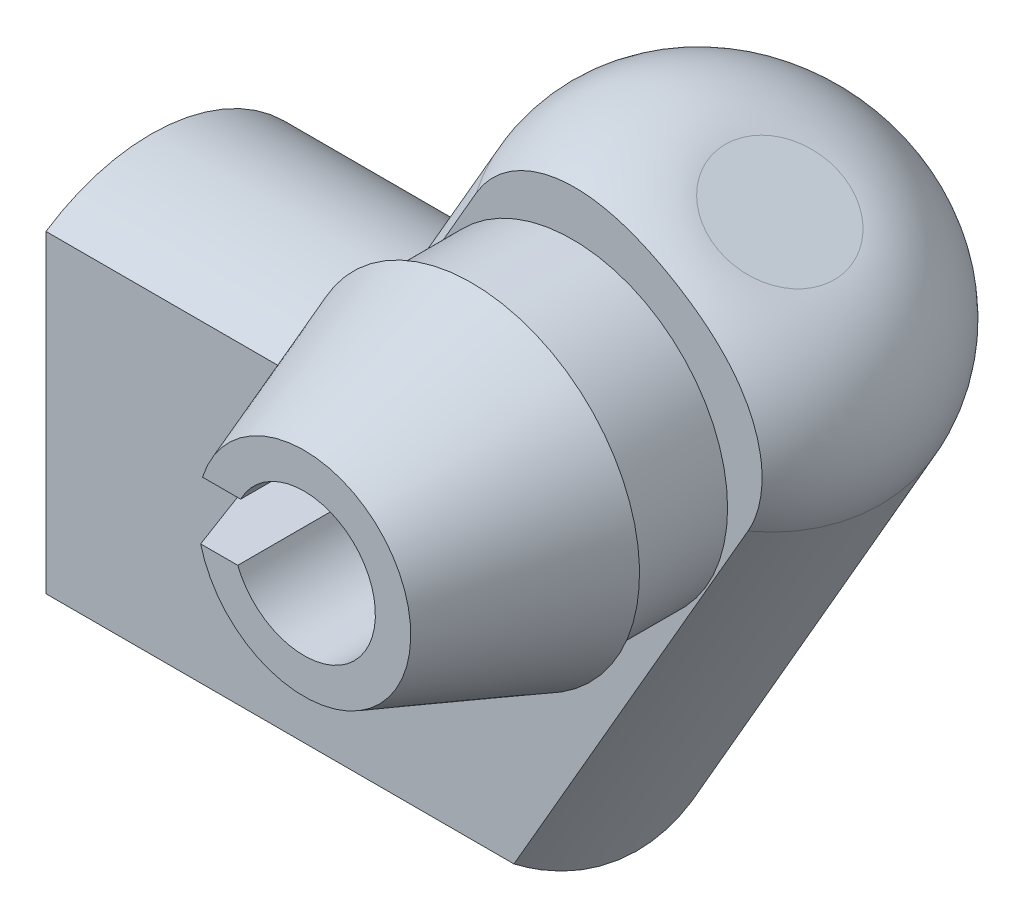
SolidWorks part; units mm, degrees
ref_plane "Front Plane" through (0, 0, 0) normal (0, 0, 1) x (1, 0, 0)
ref_plane "Top Plane" through (0, 0, 0) normal (0, 1, 0) x (1, 0, 0)
ref_plane "Right Plane" through (0, 0, 0) normal (1, 0, 0) x (0, 0, -1)
sketch "Sketch2" plane through (0, 0, 0) normal (0, 0, 1) x (1, 0, 0)
  line L0 (-4.5, 0) -> (0, 0) construction
  line L1 (0, 0) -> (3, 5.1962) construction
  line L2 (-4.5, 0) -> (0, 0)
  line L3 (0, 0) -> (3, 5.1962)
  dimension "D1" = 4.5
  dimension "D2" = 6
  dimension "D3" = 120
ref_plane "Plane1" through (-4.5, 0, 0) normal (1, 0, 0) x (0, 0, -1)
sketch "Sketch3" plane through (-4.5, 0, 0) normal (1, 0, 0) x (0, 0, -1)
  circle A0 centre (0, 0) radius 2.25
  dimension "D1" = 4.5
sweep "Sweep1" add profiles "Sketch3" path "Sketch2"
fillet "Fillet2" radius 1.5 1 edges at (3, 5.1962, -2.25)
sketch "Sketch4" plane through (-4.5, 0, 0) normal (-1, 0, 0) x (0, 0, 1)
  circle A0 centre (0, 0) radius 1.125
  dimension "D1" = 2.25
sketch "Sketch5" plane through (0, 0, 0) normal (0, 0, 1) x (1, 0, 0)
  line L0 (-4.5, 0) -> (1.2, 0)
  line L1 (-4.5, 1.125) -> (-4.5, -1.125) construction
  dimension "D1" = 5.7
sweep "Cut-Sweep1" cut profiles "Sketch4" path "Sketch5"
ref_plane "Plane2" through (0, 0, -1.25) normal (0, 0, 1) x (1, 0, 0)
sketch "Sketch6" plane through (0, 0, -1.25) normal (0, 0, 1) x (1, 0, 0)
  line L9 (-4.6679, 5.8534) -> (4.6291, 5.8534)
  line L10 (-4.6679, 5.8534) -> (-4.6679, -2.403)
  line L11 (-4.6679, -2.403) -> (4.6291, -2.403)
  line L12 (4.6291, 5.8534) -> (4.6291, -2.403)
extrude "Cut-Extrude1" cut sketch "Sketch6" against normal blind 3
sketch "Sketch7" plane through (0, 0, -1.25) normal (0, 0, -1) x (-1, 0, 0)
  line L0 (-3, 5.1962) -> (0, 0) construction
  line L1 (-2.3505, 5.5712) -> (-3.6495, 4.8212) construction
  line L2 (0, 0) -> (4.5, 0) construction
  line L3 (4.5, 1.8708) -> (4.5, -1.8708) construction
  circle A0 centre (-1.7774, 3.0786) radius 1.85
  dimension "D1" = 3.7
extrude "Boss-Extrude2" add sketch "Sketch7" along normal blind 1.2
sketch "Sketch8" plane through (0, 0, -2.45) normal (0, 0, -1) x (-1, 0, 0)
  circle A0 centre (-1.7774, 3.0786) radius 2
  circle A1 centre (-1.7774, 3.0786) radius 1.85 construction
  dimension "D1" = 4
extrude "Boss-Extrude3" add sketch "Sketch8" along normal blind 2 draft 20
sketch "Sketch9" plane through (0, 0, -4.45) normal (0, 0, -1) x (-1, 0, 0)
  circle A0 centre (-1.7774, 3.0786) radius 0.85
  circle A1 centre (-1.7774, 3.0786) radius 1.2721 construction
  dimension "D1" = 1.7
extrude "Cut-Extrude2" cut sketch "Sketch9" against normal blind 2.4
sketch "Sketch10" plane through (0, 0, -4.45) normal (0, 0, -1) x (-1, 0, 0)
  line L1 (-1.1013, 3.4666) -> (0.4341, 3.4666)
  line L2 (-1.1013, 3.4666) -> (-1.1013, 2.7666)
  line L3 (-1.1013, 2.7666) -> (0.4341, 2.7666)
  line L4 (0.4341, 3.4666) -> (0.4341, 2.7666)
  dimension "D1" = 0.7
extrude "Cut-Extrude3" cut sketch "Sketch10" against normal blind 2.4
ref_plane "Plane3" through (0, 0, -10) normal (0, 0, 1) x (1, 0, 0)
mirror "Mirror1" about plane through (0, 0, -10) normal (0, 0, 1) of bodies 109
delete or keep bodies "Body-Delete/Keep 1" type delete bodies bodies 109
